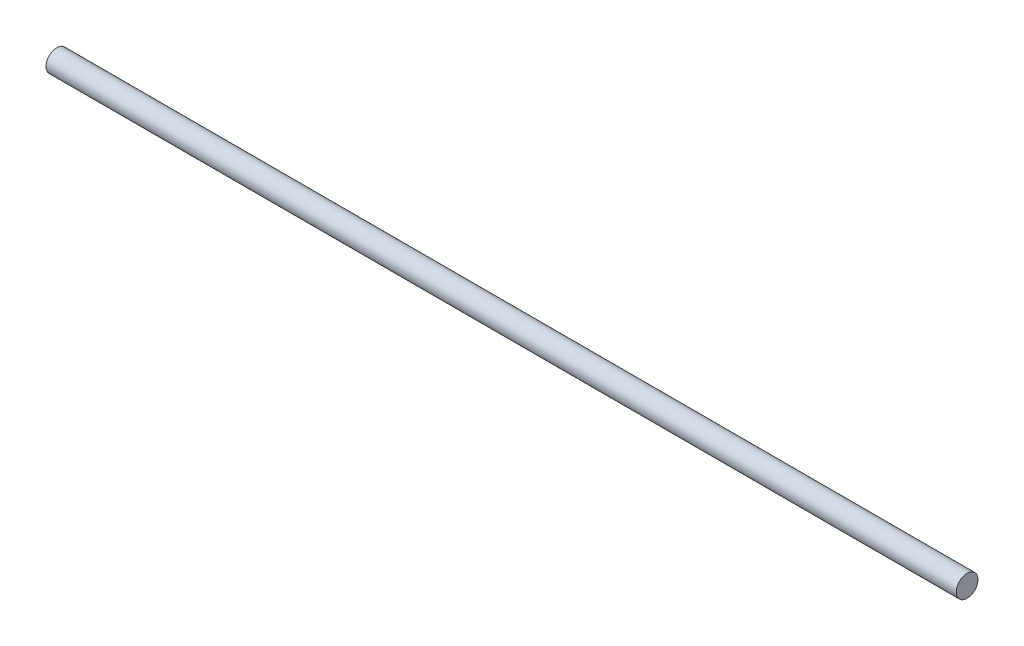
SolidWorks part; units mm, degrees
material "Aço inoxidável fundido"
ref_plane "Plano frontal" through (0, 0, 0) normal (0, 0, 1) x (1, 0, 0)
ref_plane "Plano superior" through (0, 0, 0) normal (0, 1, 0) x (1, 0, 0)
ref_plane "Plano direito" through (0, 0, 0) normal (1, 0, 0) x (0, 0, -1)
sketch "Esboço1" plane through (0, 0, 0) normal (1, 0, 0) x (0, 0, -1)
  circle A0 centre (0, 0) radius 4
  dimension "D1" = 8
extrude "Ressalto-extrusão1" add sketch "Esboço1" along normal mid plane 335
